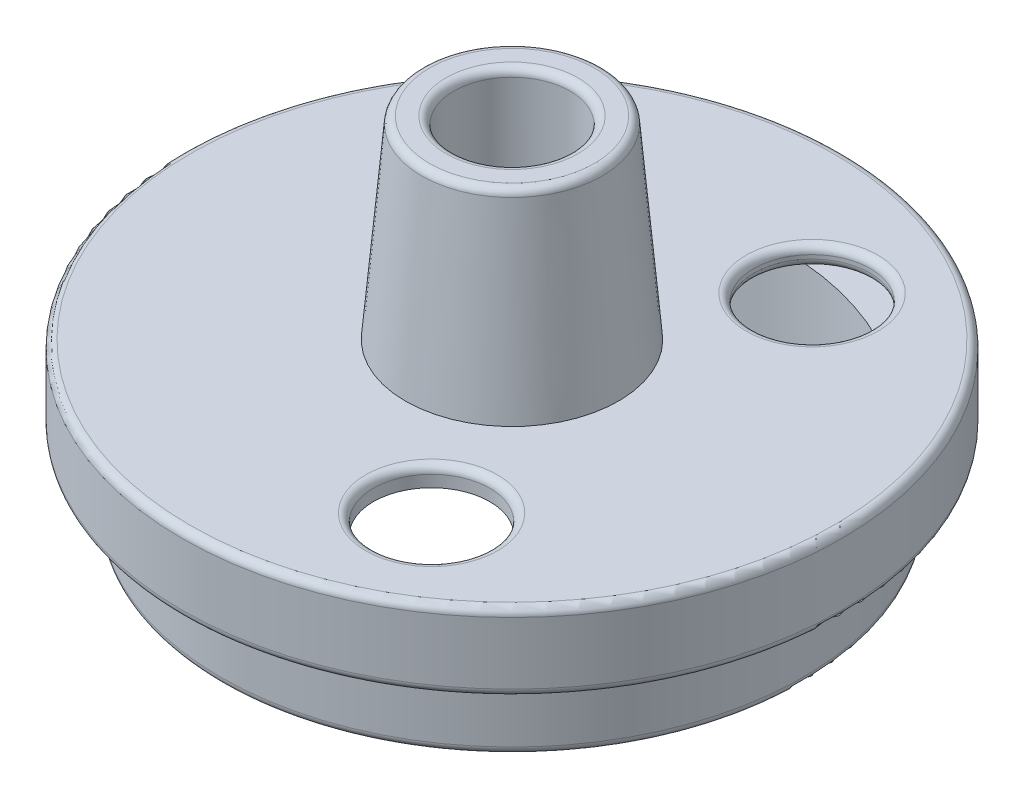
SolidWorks part; units mm, degrees
ref_plane "Front Plane" through (0, 0, 0) normal (0, 0, 1) x (1, 0, 0)
ref_plane "Top Plane" through (0, 0, 0) normal (0, 1, 0) x (1, 0, 0)
ref_plane "Right Plane" through (0, 0, 0) normal (1, 0, 0) x (0, 0, -1)
sketch "Sketch1" plane through (0, 0, 0) normal (1, 0, 0) x (0, 0, -1)
  line L0 (-8.5, -2) -> (-7.5, -2)
  line L1 (0, 0) -> (-8.5, 0)
  line L2 (0, 0) -> (0, -4) construction
  line L3 (0, -0.5) -> (-8, -0.5)
  line L4 (-8.5, 0) -> (-8.5, -2)
  line L5 (-8, -0.5) -> (-8, -1.5)
  line L6 (-8, -1.5) -> (-7, -1.5)
  line L7 (0, -4) -> (-7.5, -4) construction
  line L8 (-7.5, -2) -> (-7.5, -4)
  line L9 (-7, -1.5) -> (-7, -4)
  line L10 (0, -0.5) -> (0, 0)
  line L11 (-7, -4) -> (-7.5, -4)
  dimension "D1" = 8.5
  dimension "D2" = 2
  dimension "D3" = 7.5
  dimension "D4" = 4
  dimension "D5" = 0.5
revolve "Revolve1" add sketch "Sketch1" angle 360 about L2
sketch "Sketch2" plane through (0, 0, 0) normal (0, 1, 0) x (1, 0, 0)
  line L0 (0, 8.5) -> (0, -8.5) construction
  line L1 (-8.5, 0) -> (8.5, 0) construction
  line L2 (0, 0) -> (4.25, 7.3612) construction
  line L3 (0, 0) -> (4.25, -7.3612) construction
  circle A0 centre (0, 0) radius 8.5 construction
  circle A1 centre (2.8333, 4.9075) radius 1.5
  circle A2 centre (0, 0) radius 1.5
  circle A3 centre (2.8333, -4.9075) radius 1.5
  dimension "D1" = 3
  dimension "D2" = 3
  dimension "D5" = 3
  dimension "D3" = 30
  dimension "D4" = 30
  dimension "D6" = 8.5
  dimension "D7" = 5.6667
  dimension "D8" = 5.6667
extrude "Cut-Extrude1" cut sketch "Sketch2" against normal up to next
sketch "Sketch3" plane through (0, 0, 0) normal (0, 1, 0) x (1, 0, 0)
  circle A0 centre (0, 0) radius 1.5
  circle A1 centre (0, 0) radius 2.75
  dimension "D2" = 3
  dimension "D3" = 5.5
extrude "Boss-Extrude1" add sketch "Sketch3" along normal blind 5
draft "Draft2" type of draft neutral plane draft angle 5 faces to draft 1 face at (0, 5, 2.75) neutral plane through (0, 0, 0) neutral plane normal (0, 1, 0) parameters "D1"=5
fillet "Fillet1" radius 0.2 9 edges at (0, -4, 7) (0, -4, 7.5) (0, -2, 8.5) (2.8333, -0.5, -6.4075) (2.8333, 0, -3.4075) (0, 5, 2.3126) (0, 5, 1.5) (0, 0, 8.5) (2.8333, 0, 6.4075)
equation "\"D7@Sketch2\"=\"D6@Sketch2\"/3*2"
equation "\"D8@Sketch2\"=\"D6@Sketch2\"/3*2"
